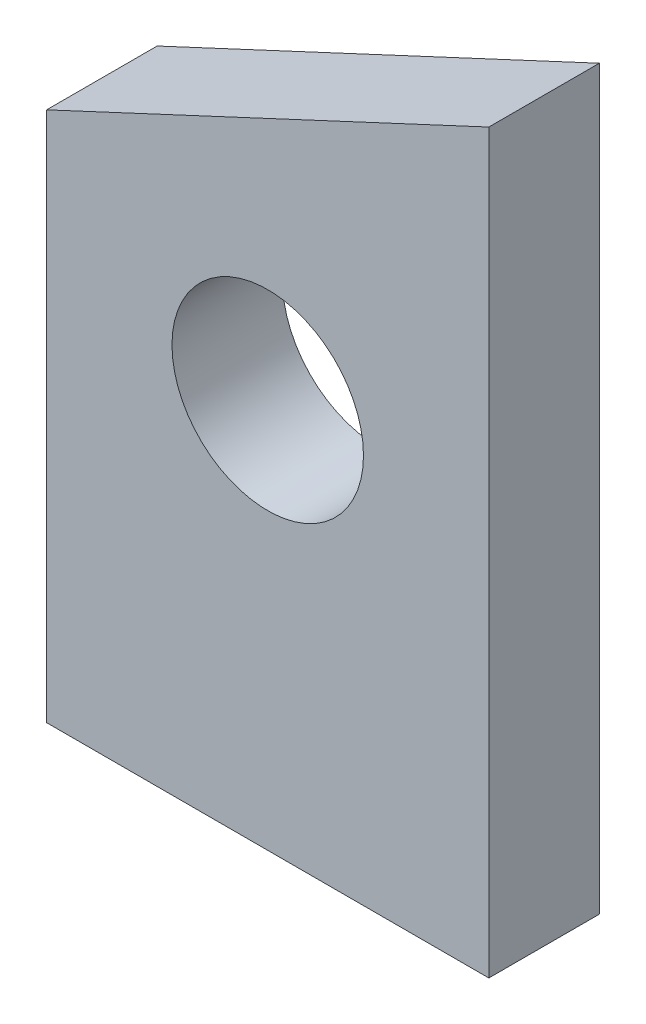
SolidWorks part; units mm, degrees
material "AISI 1020 Steel, Cold Rolled"
ref_plane "Front Plane" through (0, 0, 0) normal (0, 0, 1) x (1, 0, 0)
ref_plane "Top Plane" through (0, 0, 0) normal (0, 1, 0) x (1, 0, 0)
ref_plane "Right Plane" through (0, 0, 0) normal (1, 0, 0) x (0, 0, -1)
sketch "Sketch2" plane through (0, 0, 0) normal (0, 1, 0) x (1, 0, 0)
  line L1 (0, 0) -> (12.7, 0)
  line L2 (0, 0) -> (0, -3.175)
  line L3 (0, -3.175) -> (12.7, -3.175)
  line L4 (12.7, 0) -> (12.7, -3.175)
  dimension "D1" = 12.7
  dimension "D2" = 3.175
extrude "Boss-Extrude1" add sketch "Sketch2" along normal blind 63.5
sketch "Sketch3" plane through (0, 0, 3.175) normal (0, 0, -1) x (-1, 0, 0)
  line L0 (-6.35, 63.5) -> (-6.35, 0) construction
  line L1 (-12.7, 63.5) -> (0, 63.5) construction
  line L2 (-12.7, 0) -> (0, 0) construction
  line L3 (-12.7, 21.1648) -> (0, 15.2427)
  line L4 (-12.7, 63.5) -> (-12.7, 0) construction
  line L5 (5.3967, 12.7261) -> (-58.9511, 42.732) construction
  line L6 (0, 63.5) -> (0, 0) construction
  line L7 (0, 15.2427) -> (0, 63.5)
  line L8 (0, 63.5) -> (-12.7, 63.5)
  line L9 (-12.7, 63.5) -> (-12.7, 21.1648)
  circle A0 centre (-6.35, 11.1973) radius 2.75
  dimension "D1" = 5.5
extrude "Cut-Extrude1" cut sketch "Sketch3" along normal up to next
